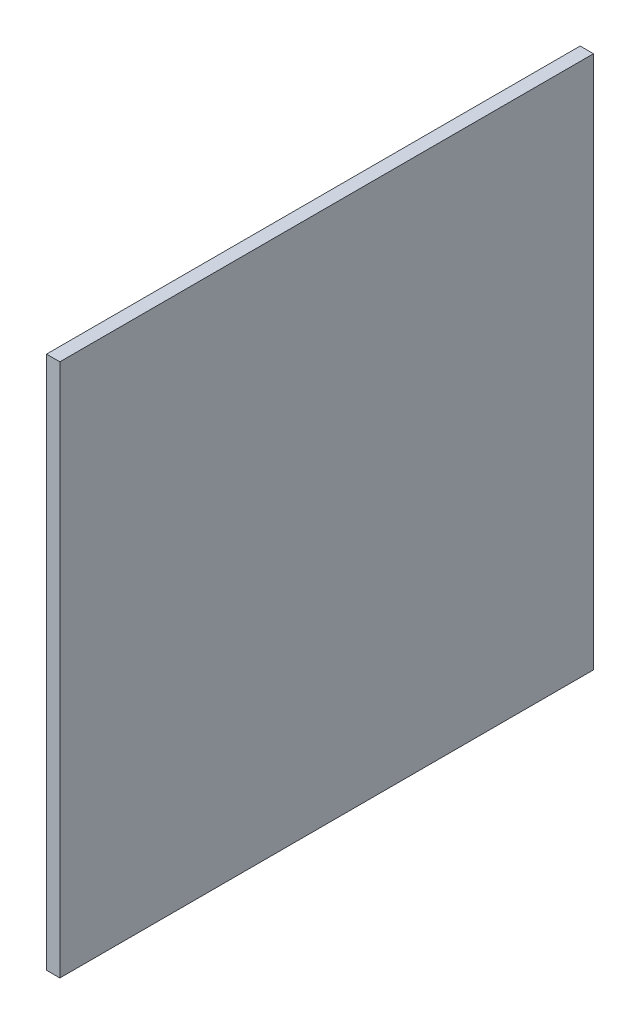
SolidWorks part; units mm, degrees
ref_plane "Front Plane" through (0, 0, 0) normal (0, 0, 1) x (1, 0, 0)
ref_plane "Top Plane" through (0, 0, 0) normal (0, 1, 0) x (1, 0, 0)
ref_plane "Right Plane" through (0, 0, 0) normal (1, 0, 0) x (0, 0, -1)
sketch "Sketch1" plane through (0, 0, 0) normal (1, 0, 0) x (0, 0, -1)
  line L1 (-200, -200) -> (200, -200)
  line L2 (-200, -200) -> (-200, 200)
  line L3 (-200, 200) -> (200, 200)
  line L4 (200, -200) -> (200, 200)
  line L5 (-200, -200) -> (200, 200) construction
  line L6 (-200, 200) -> (200, -200) construction
  point P0 (0, 0)
extrude "Boss-Extrude1" add sketch "Sketch1" along normal blind 10
